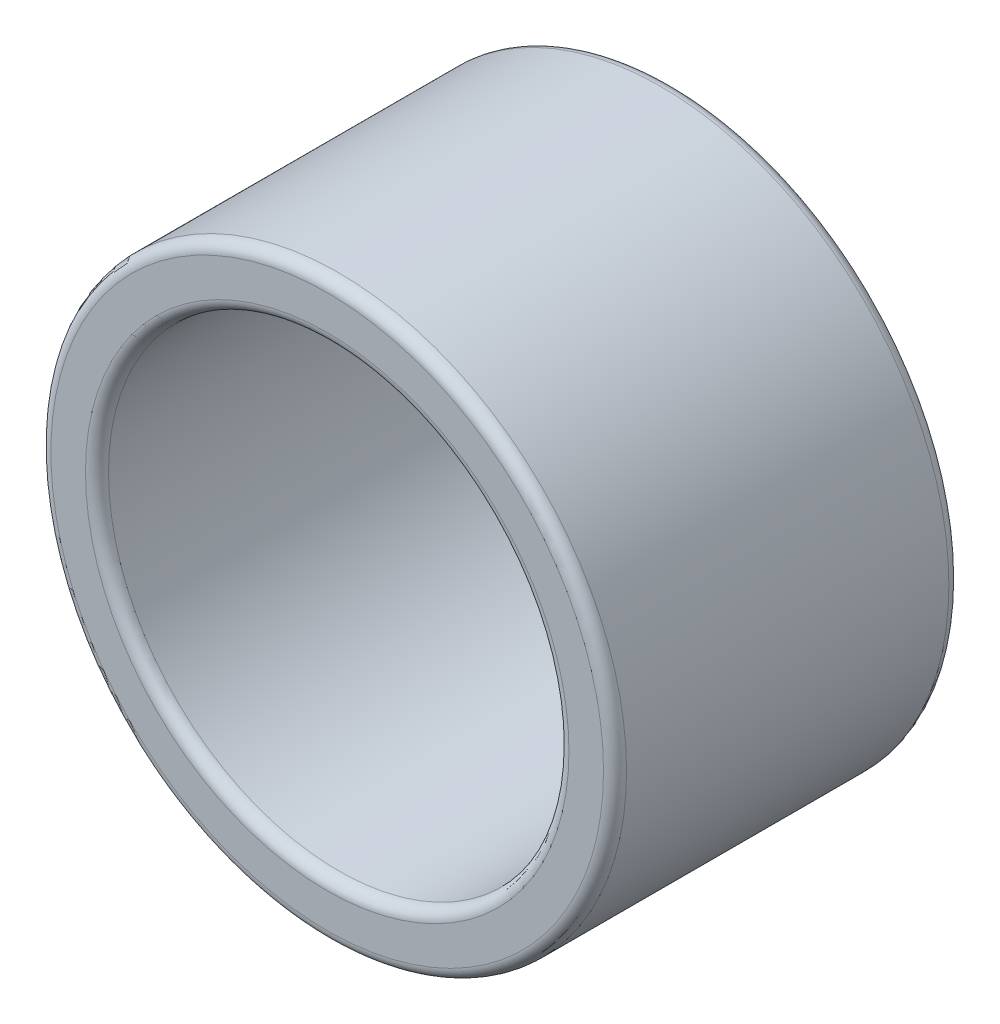
SolidWorks part; units mm, degrees
ref_plane "Front" through (0, 0, 0) normal (0, 0, 1) x (1, 0, 0)
ref_plane "Top" through (0, 0, 0) normal (0, 1, 0) x (1, 0, 0)
ref_plane "Right" through (0, 0, 0) normal (1, 0, 0) x (0, 0, -1)
sketch "Sketch1" plane through (0, 0, 0) normal (0, 0, 1) x (1, 0, 0)
  circle A0 centre (0, 0) radius 6
  circle A1 centre (0, 0) radius 7.5
  dimension "D1" = 12
  dimension "D2" = 15
extrude "Boss-Extrude1" add sketch "Sketch1" against normal blind 9
fillet "Fillet1" radius 0.3 4 edges at (7.5, 0, 0) (7.5, 0, -9) (6, 0, 0) (6, 0, -9)
